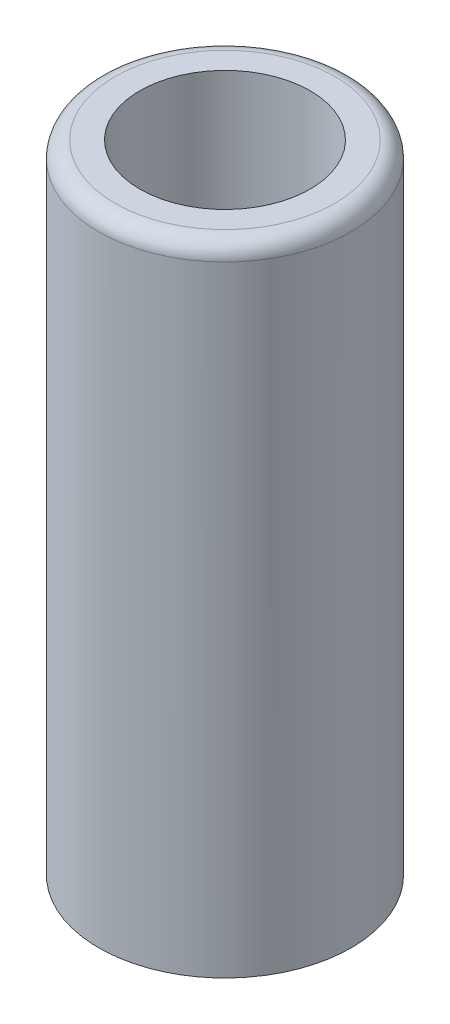
SolidWorks part; units mm, degrees
ref_plane "Front Plane" through (0, 0, 0) normal (0, 0, 1) x (1, 0, 0)
ref_plane "Top Plane" through (0, 0, 0) normal (0, 1, 0) x (1, 0, 0)
ref_plane "Right Plane" through (0, 0, 0) normal (1, 0, 0) x (0, 0, -1)
sketch "Sketch1" plane through (0, 0, 0) normal (0, 1, 0) x (1, 0, 0)
  circle A0 centre (0, 0) radius 15.375
  circle A1 centre (0, 0) radius 10.375
  dimension "D1" = 20.75
  dimension "D2" = 30.75
extrude "Boss-Extrude1" add sketch "Sketch1" along normal blind 25
sketch "Sketch3" plane through (0, 0, 0) normal (0, -1, 0) x (1, 0, 0)
  circle A0 centre (0, 0) radius 15.375
  point P3 (-32.6062, 6.4071)
extrude "Boss-Extrude2" add sketch "Sketch3" along normal blind 52.5
fillet "Fillet1" radius 2 2 edges at (0, 25, 15.375) (0, 0, 10.375)
